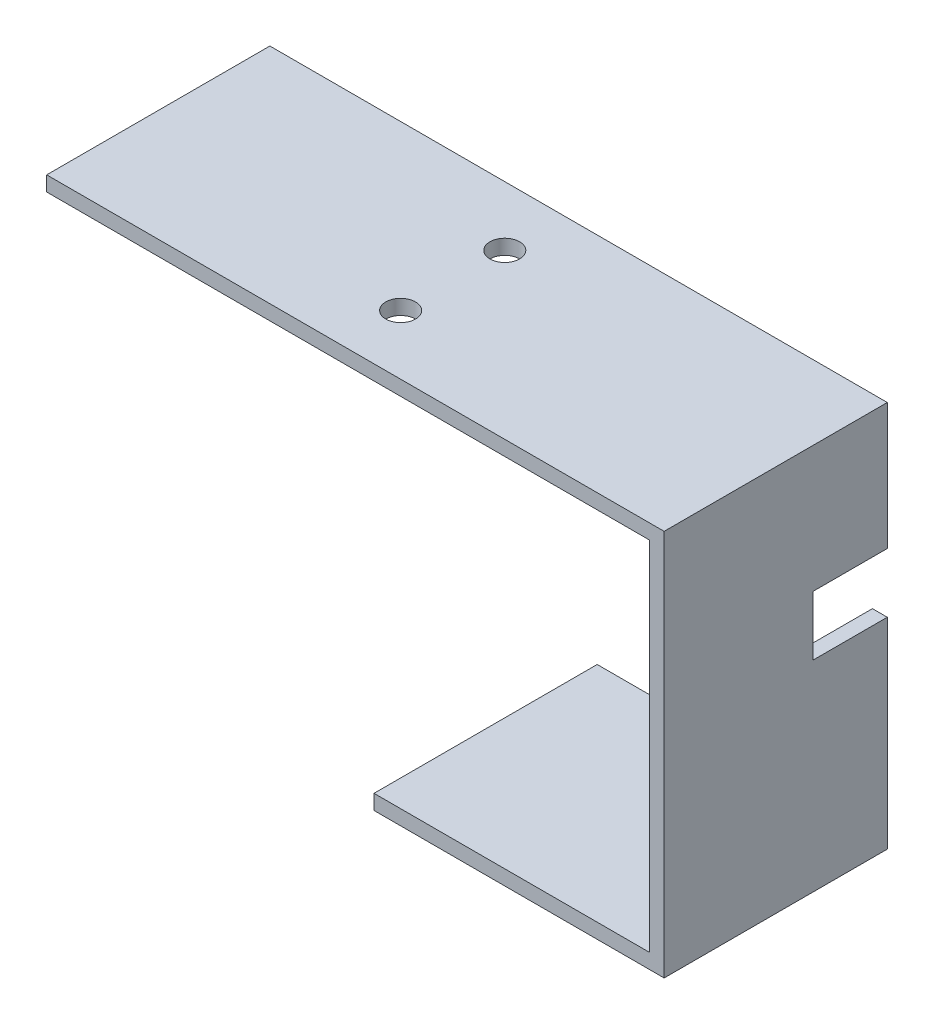
SolidWorks part; units mm, degrees
ref_plane "前视基准面" through (0, 0, 0) normal (0, 0, 1) x (1, 0, 0)
ref_plane "上视基准面" through (0, 0, 0) normal (0, 1, 0) x (1, 0, 0)
ref_plane "右视基准面" through (0, 0, 0) normal (1, 0, 0) x (0, 0, -1)
sketch "草图2" plane through (0, 0, 0) normal (0, 0, 1) x (1, 0, 0)
  line L0 (-81, 0) -> (0, 0)
  line L1 (0, 0) -> (0, -48)
  line L2 (0, -48) -> (-37, -48)
  dimension "D1" = 81
  dimension "D2" = 48
  dimension "D3" = 37
extrude "拉伸-薄壁1" add sketch "草图2" along normal blind 30 thin thin type one direction reverse wall 2
sketch "草图3" plane through (2, 0, 0) normal (1, 0, 0) x (0, 0, -1)
  line L0 (0, -23) -> (-10, -23)
  line L1 (0, 2) -> (0, -50) construction
  line L2 (-10, -23) -> (-10, -15)
  line L3 (-10, -15) -> (0, -15)
  line L4 (-30, -50) -> (0, -50) construction
  line L5 (0, -15) -> (0, -23)
  dimension "D1" = 27
  dimension "D2" = 8
  dimension "D3" = 10
extrude "切除-拉伸1" cut sketch "草图3" against normal blind 30
sketch "草图4" plane through (0, 2, 0) normal (0, 1, 0) x (1, 0, 0)
  line L0 (-81, -30) -> (2, -30) construction
  line L1 (-81, 0) -> (2, 0) construction
  circle A0 centre (-41.4202, -8) radius 2
  circle A1 centre (-41.4202, -22) radius 2
  dimension "D1" = 8
  dimension "D2" = 4
  dimension "D3" = 8
  dimension "D4" = 4
extrude "切除-拉伸2" cut sketch "草图4" against normal blind 10
